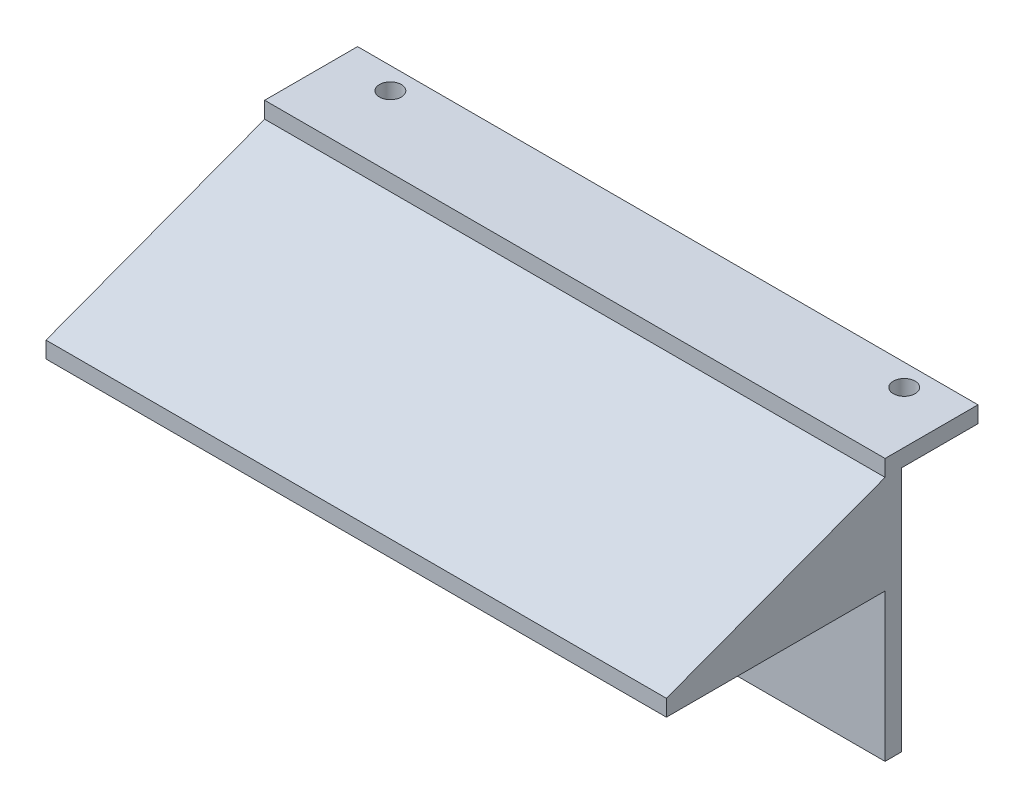
SolidWorks part; units mm, degrees
ref_plane "Plan de face" through (0, 0, 0) normal (0, 0, 1) x (1, 0, 0)
ref_plane "Plan de dessus" through (0, 0, 0) normal (0, 1, 0) x (1, 0, 0)
ref_plane "Plan de droite" through (0, 0, 0) normal (1, 0, 0) x (0, 0, -1)
sketch "Esquisse1" plane through (0, 0, 0) normal (0, 1, 0) x (1, 0, 0)
  line L0 (-39.3794, 43.7892) -> (-46.8794, 43.7892)
  line L1 (-46.8794, 43.7892) -> (-50.8794, 43.7892)
  line L2 (-140.8794, 43.7892) -> (-144.8794, 43.7892)
  line L3 (-50.8794, 43.7892) -> (-140.8794, 43.7892)
  line L4 (-144.8794, 43.7892) -> (-152.8794, 43.7892)
  line L5 (-39.3794, 43.7892) -> (-39.3794, 33.7892)
  line L6 (-39.3794, 33.7892) -> (-152.8794, 33.7892)
  line L7 (-152.8794, 33.7892) -> (-152.8794, 43.7892)
  line L8 (-152.8794, 43.7892) -> (-152.8794, 47.7892)
  line L9 (-39.3794, 43.7892) -> (-39.3794, 47.7892)
  line L10 (-39.3794, 47.7892) -> (-152.8794, 47.7892)
  circle A0 centre (-48.8794, 43.7892) radius 2
  circle A1 centre (-142.8794, 43.7892) radius 2
  dimension "D1" = 7.5
  dimension "D2" = 4
  dimension "D3" = 90
  dimension "D4" = 4
extrude "Boss.-Extru.1" add sketch "Esquisse1" along normal blind 3 contours A1 L3 A0 L0 L9 L10 L8 L4 | A1 L4 L7 L6 L5 L0 A0 L3
sketch "Esquisse2" plane through (0, 0, -33.7892) normal (0, 0, 1) x (1, 0, 0)
  line L0 (-152.8794, 3) -> (-39.3794, 3)
  line L1 (-39.3794, 3) -> (-39.3794, 0)
  line L2 (-39.3794, 0) -> (-152.8794, 0) construction
  line L3 (-39.3794, 3) -> (-39.3794, 0) construction
  line L4 (-152.8794, 3) -> (-152.8794, 0)
  line L5 (-152.8794, 0) -> (-39.3794, 0)
  line L6 (-152.8794, 0) -> (-152.8794, -45)
  line L7 (-39.3794, -45) -> (-39.3794, 0)
  line L8 (-39.3794, -45) -> (-152.8794, -45)
  line M1 (-152.8794, 0) -> (-39.3794, 0)
  line M2 (-39.3794, 0) -> (-39.3794, 3)
  line M3 (-39.3794, 3) -> (-152.8794, 3)
  line M4 (-152.8794, 3) -> (-152.8794, 0)
extrude "Boss.-Extru.2" add sketch "Esquisse2" along normal blind 3 contours L8 L7 L6 M1 | M4 M1 M2 M3 | L4 L0 L1
sketch "Esquisse3" plane through (0, 0, -30.7892) normal (0, 0, 1) x (1, 0, 0)
  line L0 (-152.8794, 3) -> (-152.8794, 0)
  line L1 (-152.8794, 3) -> (-152.8794, -45) construction
  line L2 (-152.8794, 0) -> (-152.8794, -18)
  line L3 (-152.8794, 0) -> (-39.3794, 0)
  line L6 (-39.3794, 0) -> (-39.3794, -18)
  line L7 (-39.3794, -45) -> (-39.3794, 3) construction
  line L8 (-39.3794, -18) -> (-152.8794, -18)
  line M4 (-39.3794, -45) -> (-39.3794, 3)
  line M6 (-152.8794, 3) -> (-152.8794, -45)
  dimension "D1" = 3
  dimension "D2" = 18
extrude "Boss.-Extru.3" add sketch "Esquisse3" along normal blind 40 contours L8 L3 M4 M6
sketch "Esquisse5" plane through (-152.8794, 0, 0) normal (-1, 0, 0) x (0, 0, 1)
  line L0 (9.2108, -18) -> (9.2108, -15)
  line L5 (9.2108, 0) -> (9.2108, -18) construction
  line L6 (9.2108, -15) -> (-30.7892, 0)
  line L7 (-30.7892, 0) -> (9.2108, 0)
  line L8 (9.2108, 0) -> (-30.7892, 0) construction
  line L9 (9.2108, 0) -> (9.2108, -15)
  line M9 (9.2108, -18) -> (9.2108, 0)
  line M10 (9.2108, 0) -> (-30.7892, 0)
extrude "Enlèv. mat.-Extru.1" cut sketch "Esquisse5" against normal through all contours L6 M9 M10
